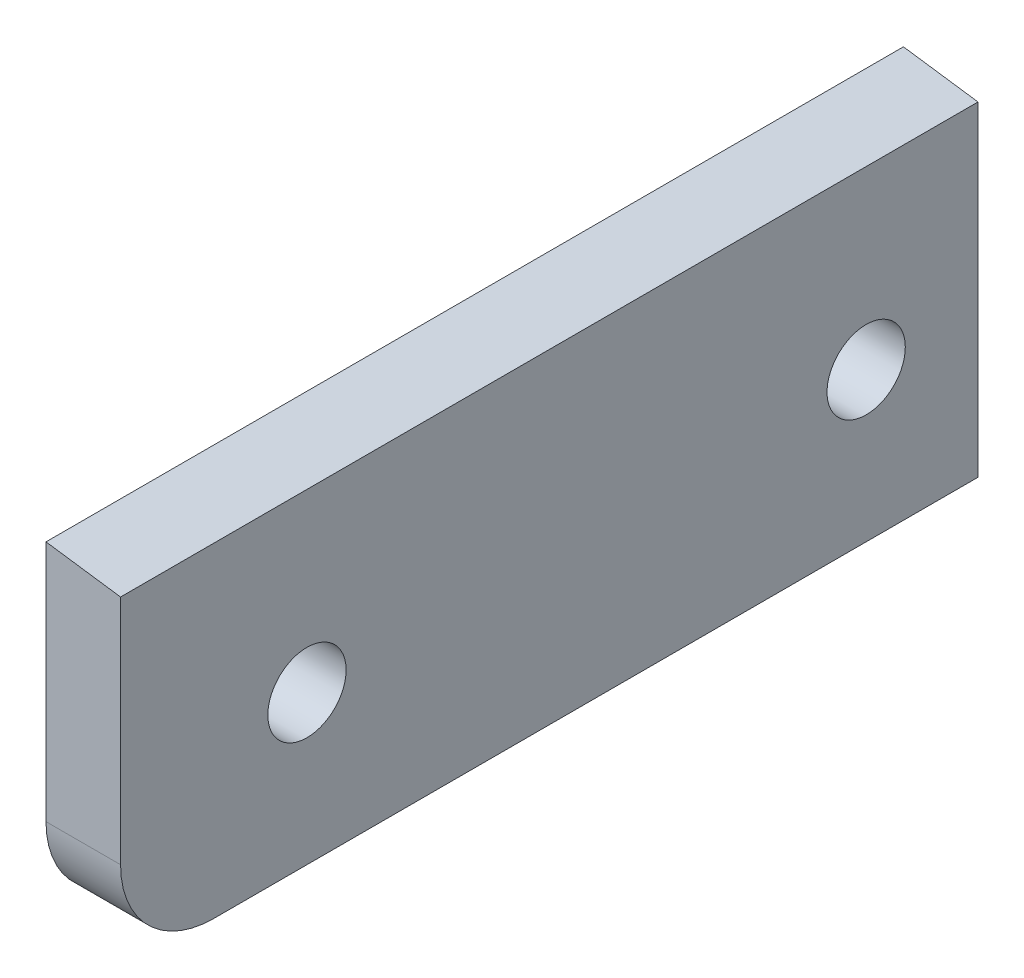
SolidWorks part; units mm, degrees
ref_plane "Frontal" through (0, 0, 0) normal (0, 0, 1) x (1, 0, 0)
ref_plane "Horizontal" through (0, 0, 0) normal (0, 1, 0) x (1, 0, 0)
ref_plane "Vertical" through (0, 0, 0) normal (1, 0, 0) x (0, 0, -1)
sketch "Esquisse1" plane through (0, 0, 0) normal (0, 0, 1) x (1, 0, 0)
  line L0 (0, 0) -> (4, 0)
  line L1 (4, 0) -> (4, 17.4378)
  line L2 (0, 0) -> (0, 18)
  line L3 (0, 18) -> (4, 17.4378)
  line L4 (0, 18) -> (66.3935, 18) construction
  dimension "D1" = 18
  dimension "D2" = 4
  dimension "D3" = 8
extrude "Extrusion1" add sketch "Esquisse1" along normal blind 46
fillet "Congé1" radius 5 1 edges at (2, 0, 46)
hole_wizard "Trou taraudé M51" positions "Esquisse3" profile "Esquisse2" tap size "M5" standard "ISO" end condition through all
sketch "Esquisse3" plane through (4, 0, 0) normal (1, 0, 0) x (0, 0, -1)
  line L0 (4.5763, 8) -> (-32.6286, 8) construction
  line L1 (0, 0) -> (0, 17.4378) construction
  line L2 (-41, 0) -> (0, 0) construction
  point P0 (-6, 8)
  point P4 (-36, 8)
  dimension "D1" = 6
  dimension "D2" = 30
  dimension "D3" = 8
sketch "Esquisse2" plane through (4, 8, 6) normal (0, 1, 0) x (0, 0, -1)
  line L0 (0, 0) -> (0, 4)
  line L1 (0, 4) -> (2.1, 4)
  line L2 (2.1, 4) -> (2.1, 0)
  line L5 (2.1, 0) -> (0, 0)
  line L11 (0, -6.35) -> (0, 107.95) construction
  dimension "Diamètre du trou pour taraudage jusqu'au prochain" = 4.2
  dimension "Profondeur du trou pour taraudage jusqu'au prochain" = 4
cosmetic thread "Filetage de perçage1" parameters "D2"=5
cosmetic thread "Filetage de perçage2" parameters "D2"=5
